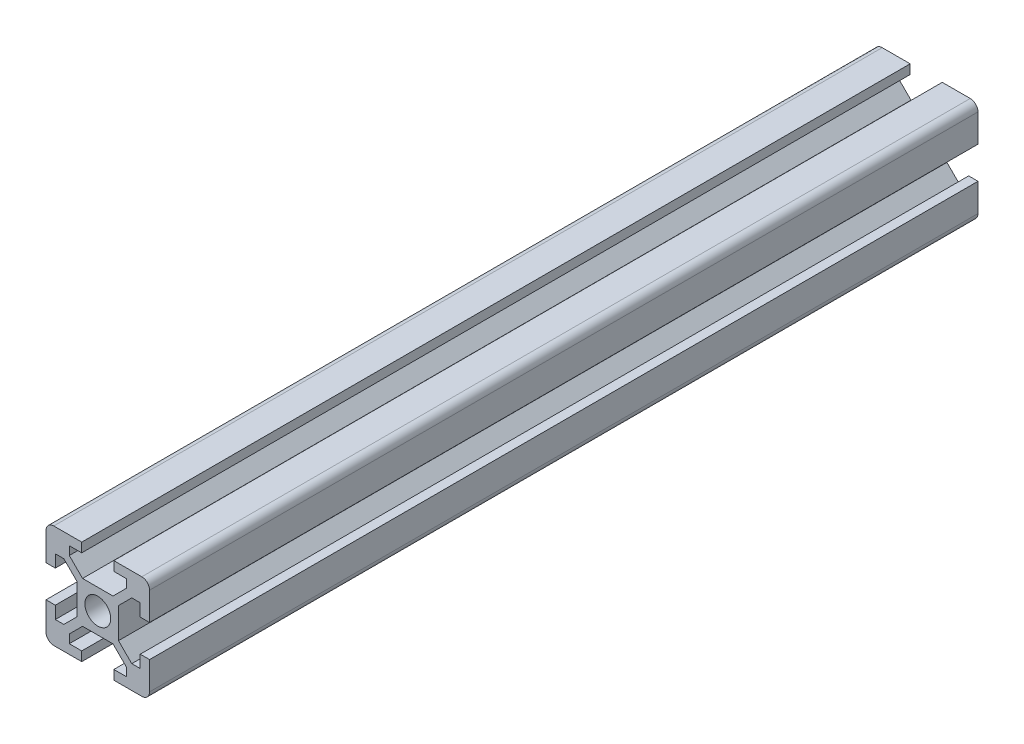
SolidWorks part; units mm, degrees
ref_plane "前视基准面" through (0, 0, 0) normal (0, 0, 1) x (1, 0, 0)
ref_plane "上视基准面" through (0, 0, 0) normal (0, 1, 0) x (1, 0, 0)
ref_plane "右视基准面" through (0, 0, 0) normal (1, 0, 0) x (0, 0, -1)
sketch "草图1" plane through (0, 0, 0) normal (0, 0, 1) x (1, 0, 0)
  line L0 (5.5, -8.2) -> (5.5, -6.5607)
  line L1 (-8.5, -10) -> (-3.1, -10)
  line L2 (-10, -8.5) -> (-10, -3.1)
  line L3 (-8.5, 10) -> (-3.1, 10)
  line L4 (10, -8.5) -> (10, -3.1)
  line L5 (-10, -10) -> (10, 10) construction
  line L6 (-10, 10) -> (10, -10) construction
  line L7 (8.2, 5.5) -> (6.5607, 5.5)
  line L8 (-2.9393, 4) -> (2.9393, 4)
  line L9 (4, 2.9393) -> (4, -2.9393)
  line L10 (2.9393, -4) -> (-2.9393, -4)
  line L11 (-4, -2.9393) -> (-4, 2.9393)
  line L12 (5.5, 6.5607) -> (5.5, 8.2)
  line L13 (6.5607, -5.5) -> (8.2, -5.5)
  line L14 (-8.2, -5.5) -> (-6.5607, -5.5)
  line L15 (-5.5, -6.5607) -> (-5.5, -8.2)
  line L16 (-5.5, 8.2) -> (-5.5, 6.5607)
  line L17 (-6.5607, 5.5) -> (-8.2, 5.5)
  line L18 (4, 2.9393) -> (6.5607, 5.5)
  line L19 (2.9393, 4) -> (5.5, 6.5607)
  line L20 (2.9393, -4) -> (5.5, -6.5607)
  line L21 (-4, 2.9393) -> (-6.5607, 5.5)
  line L22 (4, -2.9393) -> (6.5607, -5.5)
  line L23 (-2.9393, 4) -> (-5.5, 6.5607)
  line L24 (-4, -2.9393) -> (-6.5607, -5.5)
  line L25 (-2.9393, -4) -> (-5.5, -6.5607)
  line L26 (8.2, 3.1) -> (8.2, 5.5)
  line L27 (8.2, 3.1) -> (10, 3.1)
  line L28 (3.1, -8.2) -> (5.5, -8.2)
  line L29 (3.1, -8.2) -> (3.1, -10)
  line L30 (8.2, -3.1) -> (10, -3.1)
  line L31 (8.2, -3.1) -> (8.2, -5.5)
  line L32 (-3.1, -8.2) -> (-3.1, -10)
  line L33 (-3.1, -8.2) -> (-5.5, -8.2)
  line L34 (-8.2, -3.1) -> (-8.2, -5.5)
  line L35 (-8.2, -3.1) -> (-10, -3.1)
  line L36 (-8.2, 3.1) -> (-10, 3.1)
  line L37 (-8.2, 3.1) -> (-8.2, 5.5)
  line L38 (-3.1, 8.2) -> (-5.5, 8.2)
  line L39 (-3.1, 8.2) -> (-3.1, 10)
  line L40 (3.1, 8.2) -> (3.1, 10)
  line L41 (3.1, 8.2) -> (5.5, 8.2)
  line L42 (10, 3.1) -> (10, 8.5)
  line L43 (3.1, 10) -> (8.5, 10)
  line L44 (-10, 3.1) -> (-10, 8.5)
  line L45 (3.1, -10) -> (8.5, -10)
  arc A0 (8.5, -10) -> (10, -8.5) centre (8.5, -8.5) ccw
  arc A1 (-10, 8.5) -> (-8.5, 10) centre (-8.5, 8.5) cw
  arc A2 (-8.5, -10) -> (-10, -8.5) centre (-8.5, -8.5) cw
  arc A3 (8.5, 10) -> (10, 8.5) centre (8.5, 8.5) cw
  circle A4 centre (0, 0) radius 2.5
  point P0 (0, 0)
  point P39 (0, 0)
  point P56 (0, 0)
  point P73 (0, 0)
  dimension "D3" = 1.5
  dimension "D4" = 4
  dimension "D1" = 20
  dimension "D2" = 20
  dimension "D5" = 4
  dimension "D6" = 4
extrude "凸台-拉伸2" add sketch "草图1" against normal blind 160
